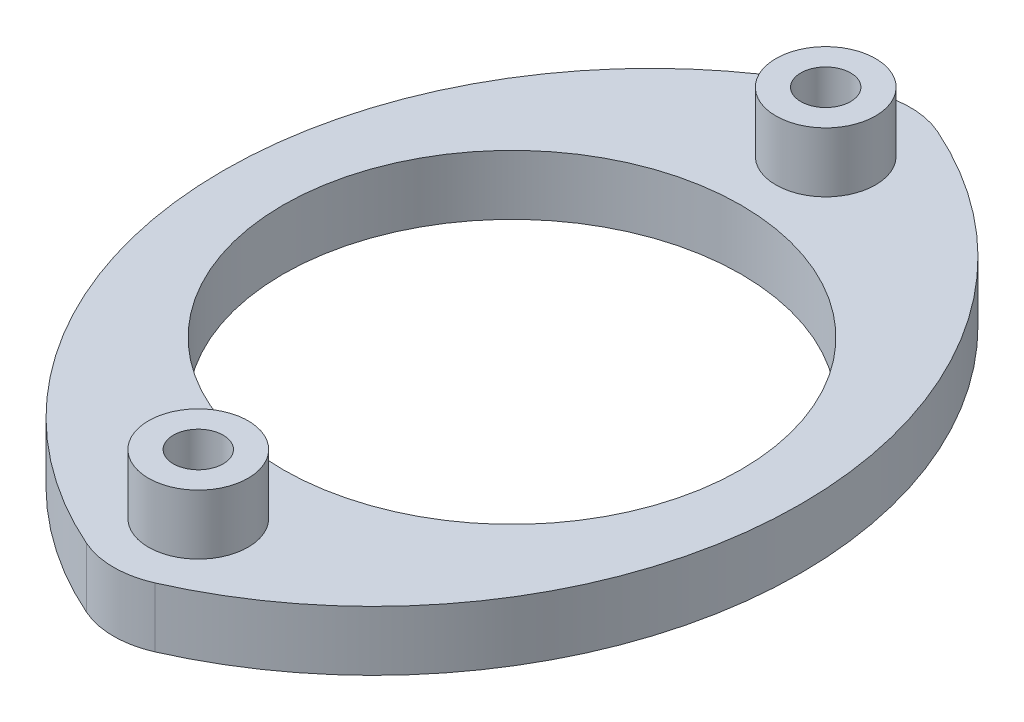
SolidWorks part; units mm, degrees
ref_plane "Front Plane" through (0, 0, 0) normal (0, 0, 1) x (1, 0, 0)
ref_plane "Top Plane" through (0, 0, 0) normal (0, 1, 0) x (1, 0, 0)
ref_plane "Right Plane" through (0, 0, 0) normal (1, 0, 0) x (0, 0, -1)
sketch "Sketch1" plane through (0, 0, 0) normal (0, 1, 0) x (1, 0, 0)
  line L0 (0, 0) -> (12.7991, 0) construction
  line L1 (0, 0) -> (0, 7.9772) construction
  circle A0 centre (0, 0) radius 15.75 construction
  circle A1 centre (0, 0) radius 10 construction
  circle A2 centre (0, 15.75) radius 1.25
  circle A3 centre (0, -15.75) radius 1.25
  circle A4 centre (0, 15.75) radius 4.25
  arc A5 (-1.7211, 19.6359) -> (-1.7211, -19.6359) centre (6.9756, 0) ccw
  circle A6 centre (0, -15.75) radius 4.25
  arc A7 (1.7211, 19.6359) -> (1.7211, -19.6359) centre (-6.9756, 0) cw
  circle A8 centre (0, 0) radius 11.5
  dimension "D1" = 20
  dimension "D2" = 31.5
  dimension "D3" = 2.5
  dimension "D4" = 3
  dimension "D5" = 3
extrude "Boss-Extrude1" add sketch "Sketch1" along normal blind 3 contours A8 A4 A5 A6 | A8 A6 A7 A4 | A4 A2 | A6 A3
sketch "Sketch2" plane through (0, 3, 0) normal (0, 1, 0) x (1, 0, 0)
  circle A0 centre (0, 15.75) radius 1.25 construction
  circle A1 centre (0, 15.75) radius 1.25
  circle A2 centre (0, 15.75) radius 2.5
  dimension "D1" = 5
extrude "Boss-Extrude2" add sketch "Sketch2" along normal blind 6 from surface at -3 starting at face at (0, 0, 0)
mirror "Mirror1" about plane through (0, 0, 0) normal (0, 0, 1) of "Boss-Extrude2"
